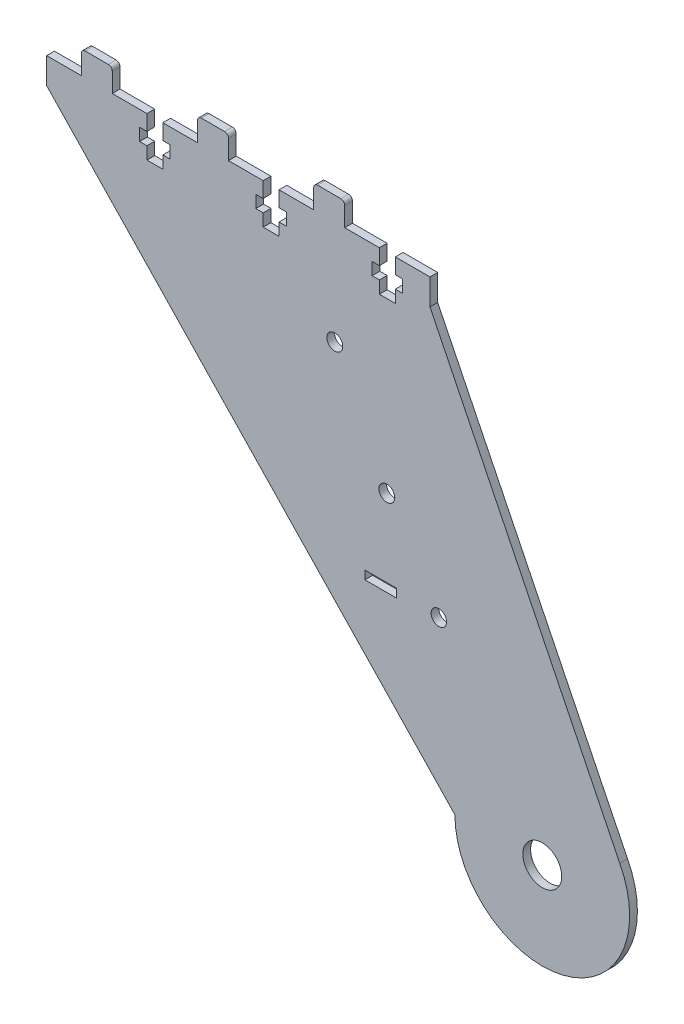
SolidWorks part; units mm, degrees
ref_plane "前视基准面" through (0, 0, 0) normal (0, 0, 1) x (1, 0, 0)
ref_plane "上视基准面" through (0, 0, 0) normal (0, 1, 0) x (1, 0, 0)
ref_plane "右视基准面" through (0, 0, 0) normal (1, 0, 0) x (0, 0, -1)
sketch "草图1" plane through (0, 0, 0) normal (0, 0, 1) x (1, 0, 0)
  line L0 (-19.7627, 31.422) -> (7.0984, -10.75) construction
  line L2 (-36.2, 66.25) -> (-36.2, 56.15) construction
  line L15 (-38.25, 64.25) -> (-38.25, 60.25)
  line L16 (-38.25, 60.25) -> (-40.15, 60.25)
  line L17 (-40.15, 60.25) -> (-40.15, 57.05)
  line L18 (-40.15, 57.05) -> (-38.25, 57.05)
  line L19 (-38.25, 57.05) -> (-38.25, 53.85)
  line L20 (-38.25, 53.85) -> (-34.15, 53.85)
  line L21 (-38.25, 64.25) -> (-47.2, 64.25)
  line L22 (-51.2, 64.25) -> (-51.2, 70.25) construction
  line L23 (-47.2, 64.25) -> (-55.2, 64.25) construction
  line L24 (-47.2, 64.25) -> (-47.2, 70.25)
  line L25 (-47.2, 70.25) -> (-55.2, 70.25)
  line L26 (-55.2, 64.25) -> (-55.2, 70.25)
  line L27 (-25.2, 64.25) -> (-17.2, 64.25) construction
  line L28 (-21.2, 64.25) -> (-21.2, 70.25) construction
  line L29 (-17.2, 64.25) -> (-17.2, 70.25)
  line L30 (-25.2, 70.25) -> (-17.2, 70.25)
  line L31 (-25.2, 64.25) -> (-25.2, 70.25)
  line L32 (-34.15, 64.25) -> (-25.2, 64.25)
  line L33 (-34.15, 57.05) -> (-34.15, 53.85)
  line L34 (-32.25, 57.05) -> (-34.15, 57.05)
  line L35 (-32.25, 60.25) -> (-32.25, 57.05)
  line L36 (-34.15, 60.25) -> (-32.25, 60.25)
  line L37 (-34.15, 64.25) -> (-34.15, 60.25)
  line L38 (-94.15, 64.25) -> (-94.15, 57.55)
  line L40 (-68.25, 64.25) -> (-68.25, 60.25)
  line L41 (-68.25, 60.25) -> (-70.15, 60.25)
  line L42 (-70.15, 60.25) -> (-70.15, 57.05)
  line L43 (-70.15, 57.05) -> (-68.25, 57.05)
  line L44 (-68.25, 57.05) -> (-68.25, 53.85)
  line L45 (-68.25, 64.25) -> (-77.2, 64.25)
  line L46 (-6.2, 66.25) -> (-6.2, 56.15) construction
  line L49 (-64.15, 53.85) -> (-68.25, 53.85)
  line L50 (-64.15, 57.05) -> (-64.15, 53.85)
  line L51 (-62.25, 57.05) -> (-64.15, 57.05)
  line L52 (-62.25, 60.25) -> (-62.25, 57.05)
  line L53 (-64.15, 60.25) -> (-62.25, 60.25)
  line L54 (-64.15, 64.25) -> (-64.15, 60.25)
  line L55 (-55.2, 64.25) -> (-64.15, 64.25)
  line L58 (-8.25, 64.25) -> (-17.2, 64.25)
  line L59 (-94.15, 64.25) -> (-85.2, 64.25)
  line L60 (-85.2, 64.25) -> (-85.2, 70.25)
  line L61 (-77.2, 70.25) -> (-85.2, 70.25)
  line L62 (-77.2, 64.25) -> (-77.2, 70.25)
  line L63 (4.8, 64.25) -> (4.8, 57.55)
  line L65 (7.0984, -10.75) -> (-7.9016, -10.75) construction
  line L66 (-8.25, 64.25) -> (-8.25, 60.25)
  line L67 (-8.25, 60.25) -> (-10.15, 60.25)
  line L68 (-10.15, 60.25) -> (-10.15, 57.05)
  line L69 (-10.15, 57.05) -> (-8.25, 57.05)
  line L70 (-8.25, 57.05) -> (-8.25, 53.85)
  line L74 (-4.15, 64.25) -> (4.8, 64.25)
  line L75 (-4.15, 53.85) -> (-8.25, 53.85)
  line L76 (-4.15, 57.05) -> (-4.15, 53.85)
  line L77 (-2.25, 57.05) -> (-4.15, 57.05)
  line L78 (-2.25, 60.25) -> (-2.25, 57.05)
  line L79 (-4.15, 60.25) -> (-2.25, 60.25)
  line L80 (-4.15, 64.25) -> (-4.15, 60.25)
  line L87 (-12.0016, -11.85) -> (-3.8016, -11.85)
  line L88 (-12.0016, -11.85) -> (-12.0016, -9.65)
  line L89 (-12.0016, -9.65) -> (-3.8016, -9.65)
  line L90 (-3.8016, -11.85) -> (-3.8016, -9.65)
  line L91 (-12.0016, -11.85) -> (-3.8016, -9.65) construction
  line L92 (-12.0016, -9.65) -> (-3.8016, -11.85) construction
  line L100 (53.7933, -42.3195) -> (4.8, 57.55)
  line L113 (-94.15, 57.55) -> (11.24, -52.75)
  line L135 (-19.7627, 31.422) -> (-19.7627, 37.422) construction
  circle A0 centre (-36.2, 66.25) radius 2.05 construction
  circle A1 centre (-19.7627, 31.422) radius 2 construction
  circle A2 centre (7.0984, -10.75) radius 2
  circle A3 centre (33.795, -52.75) radius 22.555 construction
  circle A7 centre (33.795, -52.75) radius 5.02
  circle A8 centre (-6.3322, 10.336) radius 2.05
  arc A14 (11.24, -52.75) -> (53.7933, -42.3195) centre (33.795, -52.75) ccw
  circle A20 centre (-19.7627, 37.422) radius 2.05
  point P39 (-36.2, 53.85)
  point P61 (-66.2, 53.85)
  point P91 (-6.2, 53.85)
  dimension "D17" = 10.04
  dimension "D20" = 4
  dimension "D12" = 4.1
  dimension "D5" = 4
  dimension "D6" = 2
  dimension "D7" = 3.2
  dimension "D8" = 3.2
  dimension "D9" = 15
  dimension "D10" = 8
  dimension "D11" = 6
  dimension "D13" = 8.2
  dimension "D14" = 2.2
  dimension "D15" = 10.1
  dimension "D16" = 15
extrude "凸台-拉伸1" add sketch "草图1" along normal blind 2
sketch "草图2" plane through (0, 64.25, 0) normal (0, 1, 0) x (1, 0, 0)
  line L0 (-8.25, -1) -> (-4.15, -1)
  line L1 (-8.25, -2) -> (-8.25, 0) construction
  line L2 (-4.15, -2) -> (-4.15, 0) construction
  circle A0 centre (-6.2, -1) radius 2.05
fillet "圆角1" radius 1 6 edges at (-17.2, 70.25, 1) (-25.2, 70.25, 1) (-47.2, 70.25, 1) (-55.2, 70.25, 1) (-77.2, 70.25, 1) (-85.2, 70.25, 1)
